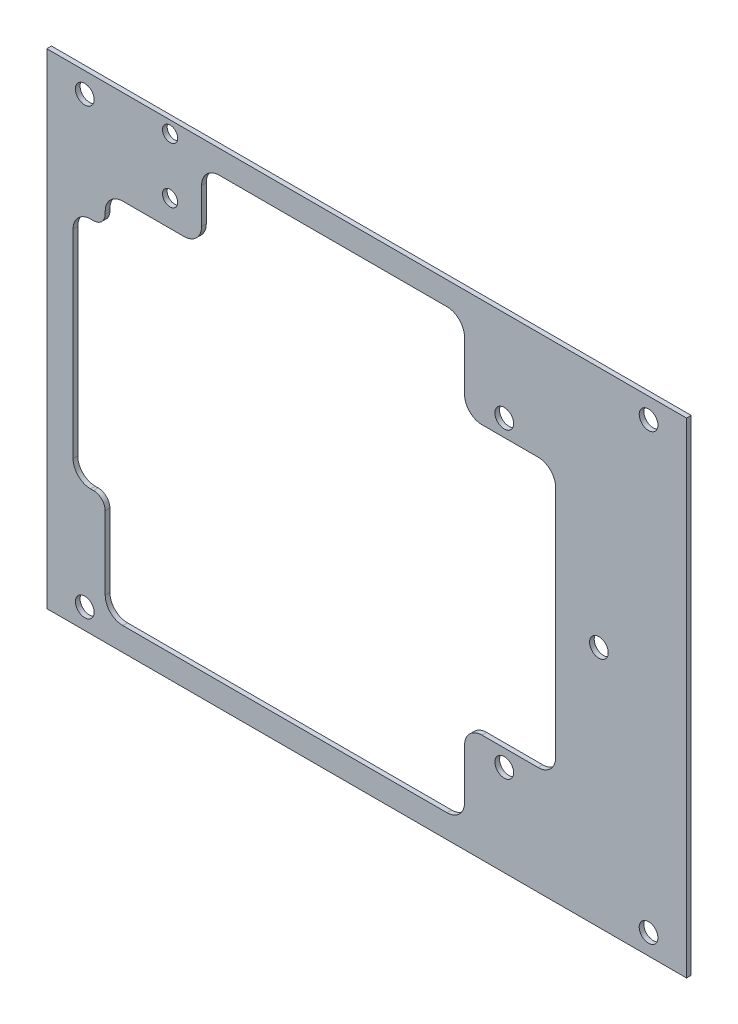
SolidWorks part; units mm, degrees
ref_plane "Front Plane" through (0, 0, 0) normal (0, 0, 1) x (1, 0, 0)
ref_plane "Top Plane" through (0, 0, 0) normal (0, 1, 0) x (1, 0, 0)
ref_plane "Right Plane" through (0, 0, 0) normal (1, 0, 0) x (0, 0, -1)
sketch "Sketch1" plane through (0, 0, 0) normal (0, 0, 1) x (1, 0, 0)
  line L0 (-50.25, -41.5) -> (-50.25, -61.5)
  line L1 (54.75, -83) -> (-54.75, -83)
  line L2 (54.75, -83) -> (54.75, 0)
  line L3 (54.75, 0) -> (-54.75, 0)
  line L4 (-54.75, -83) -> (-54.75, 0)
  line L5 (32.35, -18.5) -> (16.75, -18.5)
  line L6 (32.35, -64.5) -> (32.35, -18.5)
  line L7 (32.35, -64.5) -> (16.75, -64.5)
  line L8 (4.75, -41.5) -> (-48.75, -41.5) construction
  line L9 (-28.25, -4) -> (-28.25, -16.1)
  line L10 (-28.25, -16.1) -> (-44.75, -16.1)
  line L11 (-44.75, -16.1) -> (-44.75, -21.5)
  line L12 (-44.75, -79) -> (16.75, -79)
  line L13 (-50.25, -61.5) -> (-44.75, -61.5)
  line L14 (-44.75, -21.5) -> (-50.25, -21.5)
  line L15 (16.75, -18.5) -> (16.75, -4)
  line L16 (-50.25, -21.5) -> (-50.25, -41.5)
  line L17 (16.75, -64.5) -> (16.75, -79)
  line L18 (16.75, -4) -> (-28.25, -4)
  line L19 (-44.75, -61.5) -> (-44.75, -79)
  circle A0 centre (23.55, -67.375) radius 1.6
  circle A1 centre (23.55, -15.625) radius 1.6
  circle A2 centre (48.25, -3.5) radius 1.6
  circle A3 centre (48.25, -79.5) radius 1.6
  circle A4 centre (-48.25, -79.5) radius 1.6
  circle A5 centre (-48.25, -3.5) radius 1.6
  circle A6 centre (-33.65, -2.07) radius 1.3
  circle A7 centre (-33.65, -11.6) radius 1.3
  circle A8 centre (39.75, -41.5) radius 1.6
  dimension "D13" = 3.2
  dimension "D14" = 3.2
  dimension "D15" = 3.2
  dimension "D16" = 3.2
  dimension "D17" = 3.2
  dimension "D18" = 3.2
  dimension "D19" = 2.6
  dimension "D20" = 2.6
  dimension "D21" = 3.2
  dimension "D2" = 38
  dimension "D3" = 4
  dimension "D4" = 18.5
  dimension "D5" = 4
  dimension "D6" = 22.4
  dimension "D7" = 18.5
  dimension "D8" = 5.5
  dimension "D9" = 16.5
  dimension "D10" = 16.1
  dimension "D11" = 20
  dimension "D12" = 10
  dimension "D22" = 21.1
  dimension "D23" = 9.53
extrude "Boss-Extrude1" add sketch "Sketch1" along normal blind 0.8
fillet "Fillet1" radius 3 12 edges at (32.35, -18.5, 0.4) (16.75, -18.5, 0.4) (16.75, -4, 0.4) (-28.25, -4, 0.4) (-28.25, -16.1, 0.4) (-44.75, -16.1, 0.4) (-44.75, -79, 0.4) (16.75, -79, 0.4) (16.75, -64.5, 0.4) (32.35, -64.5, 0.4) (-50.25, -61.5, 0.4) (-50.25, -21.5, 0.4)
fillet "Fillet2" radius 2 2 edges at (-44.75, -61.5, 0.4) (-44.75, -21.5, 0.4)
